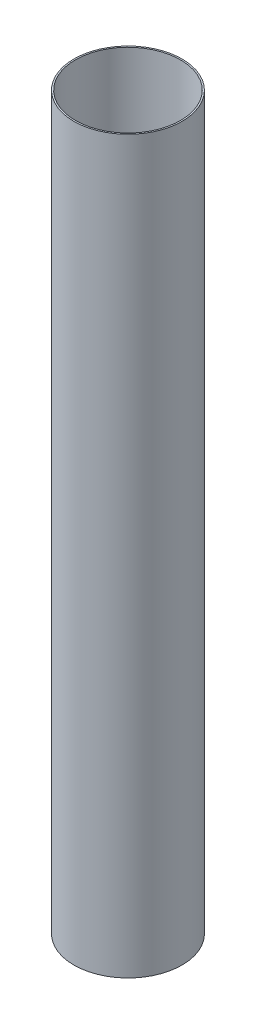
SolidWorks part; units mm, degrees
material "Hexcel AS4C (3000 Filaments)"
ref_plane "Front Plane" through (0, 0, 0) normal (0, 0, 1) x (1, 0, 0)
ref_plane "Top Plane" through (0, 0, 0) normal (0, 1, 0) x (1, 0, 0)
ref_plane "Right Plane" through (0, 0, 0) normal (1, 0, 0) x (0, 0, -1)
sketch "Sketch1" plane through (0, 0, 0) normal (0, 1, 0) x (1, 0, 0)
  circle A0 centre (0, 0) radius 50.5
  circle A1 centre (0, 0) radius 51.95
  dimension "D1" = 103.9
  dimension "D2" = 101
extrude "Boss-Extrude1" add sketch "Sketch1" along normal blind 702
